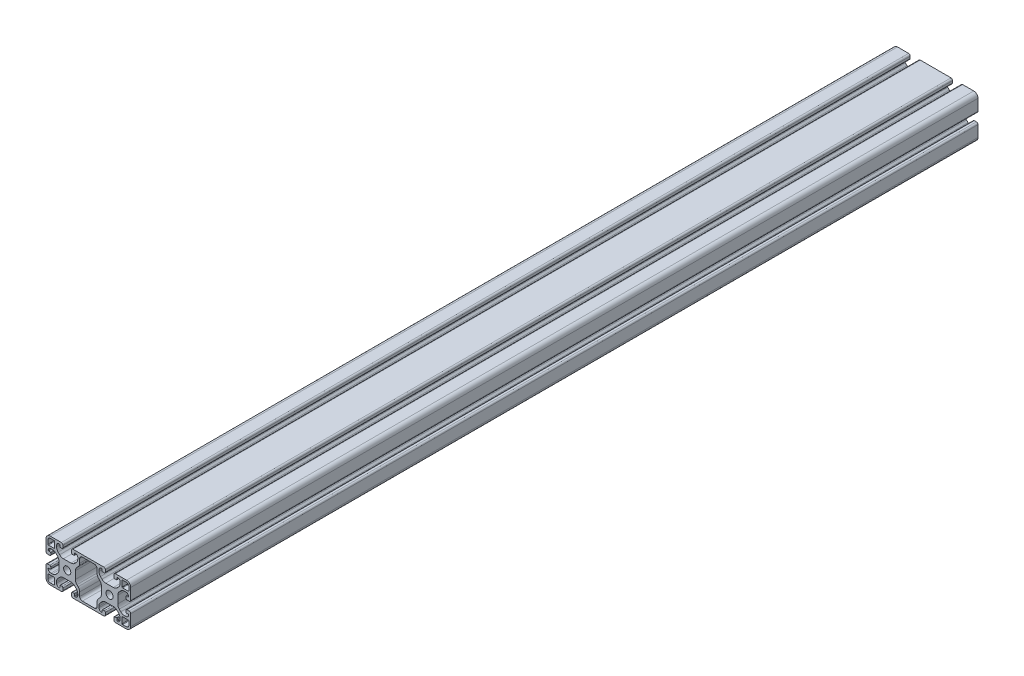
SolidWorks part; units mm, degrees
ref_plane "Plan de face" through (0, 0, 0) normal (0, 0, 1) x (1, 0, 0)
ref_plane "Plan de dessus" through (0, 0, 0) normal (0, 1, 0) x (1, 0, 0)
ref_plane "Plan de droite" through (0, 0, 0) normal (1, 0, 0) x (0, 0, -1)
ref_plane "Plan1" through (0, 0, 20) normal (0, 0, 1) x (1, 0, 0)
sketch "Esquisse1" plane through (0, 0, 20) normal (0, 0, 1) x (1, 0, 0)
  line L0 (66.5, 4.5) -> (65, 4.5)
  line L1 (64, 3.5) -> (64, 1.5)
  line L2 (65.5, 0) -> (76, 0)
  line L3 (80, 4) -> (80, 14.5)
  line L4 (78.5, 16) -> (76.5, 16)
  line L5 (75.5, 15) -> (75.5, 13.5)
  line L6 (76, 13) -> (77.5, 13)
  line L7 (75.5, 10) -> (74.1924, 10)
  line L8 (70.6569, 11.4645) -> (69.2145, 12.9069)
  line L9 (67.75, 16.4424) -> (67.75, 23.5576)
  line L10 (69.2145, 27.0931) -> (70.6569, 28.5355)
  line L11 (74.1924, 30) -> (75.5, 30)
  line L12 (77.5, 27) -> (76, 27)
  line L13 (75.5, 26.5) -> (75.5, 25)
  line L14 (76.5, 24) -> (78.5, 24)
  line L15 (80, 25.5) -> (80, 36)
  line L16 (76, 40) -> (65.5, 40)
  line L17 (64, 38.5) -> (64, 36.5)
  line L18 (65, 35.5) -> (66.5, 35.5)
  line L19 (67, 36) -> (67, 37.5)
  line L20 (70, 35.5) -> (70, 34.1924)
  line L21 (68.5355, 30.6569) -> (67.0931, 29.2145)
  line L22 (63.5576, 27.75) -> (56.4424, 27.75)
  line L23 (52.9069, 29.2145) -> (51.4645, 30.6569)
  line L24 (50, 34.1924) -> (50, 35.5)
  line L25 (53, 37.5) -> (53, 36)
  line L26 (53.5, 35.5) -> (55, 35.5)
  line L27 (56, 36.5) -> (56, 38.5)
  line L28 (54.5, 40) -> (25.5, 40)
  line L29 (24, 38.5) -> (24, 36.5)
  line L30 (25, 35.5) -> (26.5, 35.5)
  line L31 (27, 36) -> (27, 37.5)
  line L32 (30, 35.5) -> (30, 34.1924)
  line L33 (28.5355, 30.6569) -> (27.0931, 29.2145)
  line L34 (23.5576, 27.75) -> (16.4424, 27.75)
  line L35 (12.9069, 29.2145) -> (11.4645, 30.6569)
  line L36 (10, 34.1924) -> (10, 35.5)
  line L37 (13, 37.5) -> (13, 36)
  line L38 (13.5, 35.5) -> (15, 35.5)
  line L39 (16, 36.5) -> (16, 38.5)
  line L40 (14.5, 40) -> (4, 40)
  line L41 (0, 36) -> (0, 25.5)
  line L42 (1.5, 24) -> (3.5, 24)
  line L43 (4.5, 25) -> (4.5, 26.5)
  line L44 (4, 27) -> (2.5, 27)
  line L45 (4.5, 30) -> (5.8076, 30)
  line L46 (9.3431, 28.5355) -> (10.7855, 27.0931)
  line L47 (12.25, 23.5576) -> (12.25, 16.4424)
  line L48 (10.7855, 12.9069) -> (9.3431, 11.4645)
  line L49 (5.8076, 10) -> (4.5, 10)
  line L50 (2.5, 13) -> (4, 13)
  line L51 (4.5, 13.5) -> (4.5, 15)
  line L52 (3.5, 16) -> (1.5, 16)
  line L53 (0, 14.5) -> (0, 4)
  line L54 (4, 0) -> (14.5, 0)
  line L55 (16, 1.5) -> (16, 3.5)
  line L56 (15, 4.5) -> (13.5, 4.5)
  line L57 (13, 4) -> (13, 2.5)
  line L58 (10, 4.5) -> (10, 5.8076)
  line L59 (11.4645, 9.3431) -> (12.9069, 10.7855)
  line L60 (16.4424, 12.25) -> (23.5576, 12.25)
  line L61 (27.0931, 10.7855) -> (28.5355, 9.3431)
  line L62 (30, 5.8076) -> (30, 4.5)
  line L63 (27, 2.5) -> (27, 4)
  line L64 (26.5, 4.5) -> (25, 4.5)
  line L65 (24, 3.5) -> (24, 1.5)
  line L66 (25.5, 0) -> (54.5, 0)
  line L67 (56, 1.5) -> (56, 3.5)
  line L68 (55, 4.5) -> (53.5, 4.5)
  line L69 (53, 4) -> (53, 2.5)
  line L70 (50, 4.5) -> (50, 5.8076)
  line L71 (51.4645, 9.3431) -> (52.9069, 10.7855)
  line L72 (56.4424, 12.25) -> (63.5576, 12.25)
  line L73 (67.0931, 10.7855) -> (68.5355, 9.3431)
  line L74 (70, 5.8076) -> (70, 4.5)
  line L75 (67, 2.5) -> (67, 4)
  line L76 (31.8, 4.5) -> (31.8, 8.2503)
  line L77 (30.3355, 11.7858) -> (29.2145, 12.9069)
  line L78 (27.75, 16.4424) -> (27.75, 23.5576)
  line L79 (29.2145, 27.0931) -> (30.3355, 28.2142)
  line L80 (31.8, 31.7497) -> (31.8, 35.5)
  line L81 (34.3, 38) -> (45.7, 38)
  line L82 (48.2, 35.5) -> (48.2, 31.7497)
  line L83 (49.6645, 28.2142) -> (50.7855, 27.0931)
  line L84 (52.25, 23.5576) -> (52.25, 16.4424)
  line L85 (50.7855, 12.9069) -> (49.6645, 11.7858)
  line L86 (48.2, 8.2503) -> (48.2, 4.5)
  line L87 (45.7, 2) -> (34.3, 2)
  line L88 (7.7, 1.8) -> (4, 1.8)
  line L89 (1.8, 4) -> (1.8, 7.7)
  line L90 (2.3, 8.2) -> (7.7, 8.2)
  line L91 (8.2, 7.7) -> (8.2, 2.3)
  line L92 (72.3, 38.2) -> (76, 38.2)
  line L93 (78.2, 36) -> (78.2, 32.3)
  line L94 (77.7, 31.8) -> (72.3, 31.8)
  line L95 (71.8, 32.3) -> (71.8, 37.7)
  line L96 (78.2, 7.7) -> (78.2, 4)
  line L97 (76, 1.8) -> (72.3, 1.8)
  line L98 (71.8, 2.3) -> (71.8, 7.7)
  line L99 (72.3, 8.2) -> (77.7, 8.2)
  line L100 (1.8, 32.3) -> (1.8, 36)
  line L101 (4, 38.2) -> (7.7, 38.2)
  line L102 (8.2, 37.7) -> (8.2, 32.3)
  line L103 (7.7, 31.8) -> (2.3, 31.8)
  arc A0 (67, 4) -> (66.5, 4.5) centre (66.5, 4) ccw
  arc A1 (65, 4.5) -> (64, 3.5) centre (65, 3.5) ccw
  arc A2 (64, 1.5) -> (65.5, 0) centre (65.5, 1.5) ccw
  arc A3 (76, 0) -> (80, 4) centre (76, 4) ccw
  arc A4 (80, 14.5) -> (78.5, 16) centre (78.5, 14.5) ccw
  arc A5 (76.5, 16) -> (75.5, 15) centre (76.5, 15) ccw
  arc A6 (75.5, 13.5) -> (76, 13) centre (76, 13.5) ccw
  arc A7 (77.5, 13) -> (78, 12.5) centre (77.5, 12.5) cw
  arc A8 (78, 12.5) -> (75.5, 10) centre (75.5, 12.5) cw
  arc A9 (74.1924, 10) -> (70.6569, 11.4645) centre (74.1924, 15) cw
  arc A10 (69.2145, 12.9069) -> (67.75, 16.4424) centre (72.75, 16.4424) cw
  arc A11 (67.75, 23.5576) -> (69.2145, 27.0931) centre (72.75, 23.5576) cw
  arc A12 (70.6569, 28.5355) -> (74.1924, 30) centre (74.1924, 25) cw
  arc A13 (75.5, 30) -> (78, 27.5) centre (75.5, 27.5) cw
  arc A14 (78, 27.5) -> (77.5, 27) centre (77.5, 27.5) cw
  arc A15 (76, 27) -> (75.5, 26.5) centre (76, 26.5) ccw
  arc A16 (75.5, 25) -> (76.5, 24) centre (76.5, 25) ccw
  arc A17 (78.5, 24) -> (80, 25.5) centre (78.5, 25.5) ccw
  arc A18 (80, 36) -> (76, 40) centre (76, 36) ccw
  arc A19 (65.5, 40) -> (64, 38.5) centre (65.5, 38.5) ccw
  arc A20 (64, 36.5) -> (65, 35.5) centre (65, 36.5) ccw
  arc A21 (66.5, 35.5) -> (67, 36) centre (66.5, 36) ccw
  arc A22 (67, 37.5) -> (67.5, 38) centre (67.5, 37.5) cw
  arc A23 (67.5, 38) -> (70, 35.5) centre (67.5, 35.5) cw
  arc A24 (70, 34.1924) -> (68.5355, 30.6569) centre (65, 34.1924) cw
  arc A25 (67.0931, 29.2145) -> (63.5576, 27.75) centre (63.5576, 32.75) cw
  arc A26 (56.4424, 27.75) -> (52.9069, 29.2145) centre (56.4424, 32.75) cw
  arc A27 (51.4645, 30.6569) -> (50, 34.1924) centre (55, 34.1924) cw
  arc A28 (50, 35.5) -> (52.5, 38) centre (52.5, 35.5) cw
  arc A29 (52.5, 38) -> (53, 37.5) centre (52.5, 37.5) cw
  arc A30 (53, 36) -> (53.5, 35.5) centre (53.5, 36) ccw
  arc A31 (55, 35.5) -> (56, 36.5) centre (55, 36.5) ccw
  arc A32 (56, 38.5) -> (54.5, 40) centre (54.5, 38.5) ccw
  arc A33 (25.5, 40) -> (24, 38.5) centre (25.5, 38.5) ccw
  arc A34 (24, 36.5) -> (25, 35.5) centre (25, 36.5) ccw
  arc A35 (26.5, 35.5) -> (27, 36) centre (26.5, 36) ccw
  arc A36 (27, 37.5) -> (27.5, 38) centre (27.5, 37.5) cw
  arc A37 (27.5, 38) -> (30, 35.5) centre (27.5, 35.5) cw
  arc A38 (30, 34.1924) -> (28.5355, 30.6569) centre (25, 34.1924) cw
  arc A39 (27.0931, 29.2145) -> (23.5576, 27.75) centre (23.5576, 32.75) cw
  arc A40 (16.4424, 27.75) -> (12.9069, 29.2145) centre (16.4424, 32.75) cw
  arc A41 (11.4645, 30.6569) -> (10, 34.1924) centre (15, 34.1924) cw
  arc A42 (10, 35.5) -> (12.5, 38) centre (12.5, 35.5) cw
  arc A43 (12.5, 38) -> (13, 37.5) centre (12.5, 37.5) cw
  arc A44 (13, 36) -> (13.5, 35.5) centre (13.5, 36) ccw
  arc A45 (15, 35.5) -> (16, 36.5) centre (15, 36.5) ccw
  arc A46 (16, 38.5) -> (14.5, 40) centre (14.5, 38.5) ccw
  arc A47 (4, 40) -> (0, 36) centre (4, 36) ccw
  arc A48 (0, 25.5) -> (1.5, 24) centre (1.5, 25.5) ccw
  arc A49 (3.5, 24) -> (4.5, 25) centre (3.5, 25) ccw
  arc A50 (4.5, 26.5) -> (4, 27) centre (4, 26.5) ccw
  arc A51 (2.5, 27) -> (2, 27.5) centre (2.5, 27.5) cw
  arc A52 (2, 27.5) -> (4.5, 30) centre (4.5, 27.5) cw
  arc A53 (5.8076, 30) -> (9.3431, 28.5355) centre (5.8076, 25) cw
  arc A54 (10.7855, 27.0931) -> (12.25, 23.5576) centre (7.25, 23.5576) cw
  arc A55 (12.25, 16.4424) -> (10.7855, 12.9069) centre (7.25, 16.4424) cw
  arc A56 (9.3431, 11.4645) -> (5.8076, 10) centre (5.8076, 15) cw
  arc A57 (4.5, 10) -> (2, 12.5) centre (4.5, 12.5) cw
  arc A58 (2, 12.5) -> (2.5, 13) centre (2.5, 12.5) cw
  arc A59 (4, 13) -> (4.5, 13.5) centre (4, 13.5) ccw
  arc A60 (4.5, 15) -> (3.5, 16) centre (3.5, 15) ccw
  arc A61 (1.5, 16) -> (0, 14.5) centre (1.5, 14.5) ccw
  arc A62 (0, 4) -> (4, 0) centre (4, 4) ccw
  arc A63 (14.5, 0) -> (16, 1.5) centre (14.5, 1.5) ccw
  arc A64 (16, 3.5) -> (15, 4.5) centre (15, 3.5) ccw
  arc A65 (13.5, 4.5) -> (13, 4) centre (13.5, 4) ccw
  arc A66 (13, 2.5) -> (12.5, 2) centre (12.5, 2.5) cw
  arc A67 (12.5, 2) -> (10, 4.5) centre (12.5, 4.5) cw
  arc A68 (10, 5.8076) -> (11.4645, 9.3431) centre (15, 5.8076) cw
  arc A69 (12.9069, 10.7855) -> (16.4424, 12.25) centre (16.4424, 7.25) cw
  arc A70 (23.5576, 12.25) -> (27.0931, 10.7855) centre (23.5576, 7.25) cw
  arc A71 (28.5355, 9.3431) -> (30, 5.8076) centre (25, 5.8076) cw
  arc A72 (30, 4.5) -> (27.5, 2) centre (27.5, 4.5) cw
  arc A73 (27.5, 2) -> (27, 2.5) centre (27.5, 2.5) cw
  arc A74 (27, 4) -> (26.5, 4.5) centre (26.5, 4) ccw
  arc A75 (25, 4.5) -> (24, 3.5) centre (25, 3.5) ccw
  arc A76 (24, 1.5) -> (25.5, 0) centre (25.5, 1.5) ccw
  arc A77 (54.5, 0) -> (56, 1.5) centre (54.5, 1.5) ccw
  arc A78 (56, 3.5) -> (55, 4.5) centre (55, 3.5) ccw
  arc A79 (53.5, 4.5) -> (53, 4) centre (53.5, 4) ccw
  arc A80 (53, 2.5) -> (52.5, 2) centre (52.5, 2.5) cw
  arc A81 (52.5, 2) -> (50, 4.5) centre (52.5, 4.5) cw
  arc A82 (50, 5.8076) -> (51.4645, 9.3431) centre (55, 5.8076) cw
  arc A83 (52.9069, 10.7855) -> (56.4424, 12.25) centre (56.4424, 7.25) cw
  arc A84 (63.5576, 12.25) -> (67.0931, 10.7855) centre (63.5576, 7.25) cw
  arc A85 (68.5355, 9.3431) -> (70, 5.8076) centre (65, 5.8076) cw
  arc A86 (70, 4.5) -> (67.5, 2) centre (67.5, 4.5) cw
  arc A87 (67.5, 2) -> (67, 2.5) centre (67.5, 2.5) cw
  circle A88 centre (20, 20) radius 3.4
  circle A89 centre (60, 20) radius 3.4
  arc A90 (34.3, 2) -> (31.8, 4.5) centre (34.3, 4.5) cw
  arc A91 (31.8, 8.2503) -> (30.3355, 11.7858) centre (26.8, 8.2503) ccw
  arc A92 (29.2145, 12.9069) -> (27.75, 16.4424) centre (32.75, 16.4424) cw
  arc A93 (27.75, 23.5576) -> (29.2145, 27.0931) centre (32.75, 23.5576) cw
  arc A94 (30.3355, 28.2142) -> (31.8, 31.7497) centre (26.8, 31.7497) ccw
  arc A95 (31.8, 35.5) -> (34.3, 38) centre (34.3, 35.5) cw
  arc A96 (45.7, 38) -> (48.2, 35.5) centre (45.7, 35.5) cw
  arc A97 (48.2, 31.7497) -> (49.6645, 28.2142) centre (53.2, 31.7497) ccw
  arc A98 (50.7855, 27.0931) -> (52.25, 23.5576) centre (47.25, 23.5576) cw
  arc A99 (52.25, 16.4424) -> (50.7855, 12.9069) centre (47.25, 16.4424) cw
  arc A100 (49.6645, 11.7858) -> (48.2, 8.2503) centre (53.2, 8.2503) ccw
  arc A101 (48.2, 4.5) -> (45.7, 2) centre (45.7, 4.5) cw
  arc A102 (8.2, 2.3) -> (7.7, 1.8) centre (7.7, 2.3) cw
  arc A103 (4, 1.8) -> (1.8, 4) centre (4, 4) cw
  arc A104 (1.8, 7.7) -> (2.3, 8.2) centre (2.3, 7.7) cw
  arc A105 (7.7, 8.2) -> (8.2, 7.7) centre (7.7, 7.7) cw
  arc A106 (71.8, 37.7) -> (72.3, 38.2) centre (72.3, 37.7) cw
  arc A107 (76, 38.2) -> (78.2, 36) centre (76, 36) cw
  arc A108 (78.2, 32.3) -> (77.7, 31.8) centre (77.7, 32.3) cw
  arc A109 (72.3, 31.8) -> (71.8, 32.3) centre (72.3, 32.3) cw
  arc A110 (77.7, 8.2) -> (78.2, 7.7) centre (77.7, 7.7) cw
  arc A111 (78.2, 4) -> (76, 1.8) centre (76, 4) cw
  arc A112 (72.3, 1.8) -> (71.8, 2.3) centre (72.3, 2.3) cw
  arc A113 (71.8, 7.7) -> (72.3, 8.2) centre (72.3, 7.7) cw
  arc A114 (2.3, 31.8) -> (1.8, 32.3) centre (2.3, 32.3) cw
  arc A115 (1.8, 36) -> (4, 38.2) centre (4, 36) cw
  arc A116 (7.7, 38.2) -> (8.2, 37.7) centre (7.7, 37.7) cw
  arc A117 (8.2, 32.3) -> (7.7, 31.8) centre (7.7, 32.3) cw
extrude "Boss.-Extru.1" add sketch "Esquisse1" against normal blind 800
